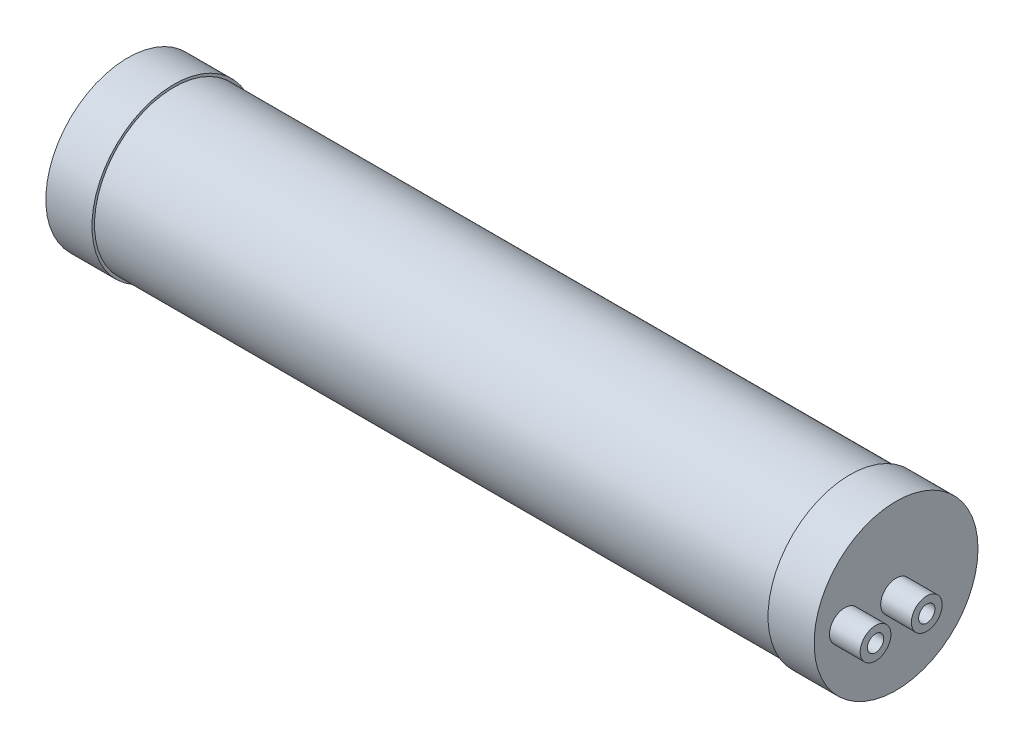
SolidWorks part; units mm, degrees
ref_plane "Front Plane" through (0, 0, 0) normal (0, 0, 1) x (1, 0, 0)
ref_plane "Top Plane" through (0, 0, 0) normal (0, 1, 0) x (1, 0, 0)
ref_plane "Right Plane" through (0, 0, 0) normal (1, 0, 0) x (0, 0, -1)
other "Configuration Table"
sketch "Sketch1" plane through (0, 0, 0) normal (1, 0, 0) x (0, 0, -1)
  circle A0 centre (0, 0) radius 31
  dimension "D1" = 62
extrude "Body" add sketch "Sketch1" along normal blind 300 from offset 150
sketch "Sketch2" plane through (0, 0, 0) normal (1, 0, 0) x (0, 0, -1)
  circle A0 centre (0, 0) radius 32
  dimension "D1" = 64
extrude "End_Cap_In" add sketch "Sketch2" along normal blind 18 from offset 150
sketch "Sketch3" plane through (0, 0, 0) normal (1, 0, 0) x (0, 0, -1)
  circle A0 centre (0, 0) radius 32
  dimension "D1" = 64
extrude "End_Cap_Out" add sketch "Sketch3" along normal blind 18 from offset 132
sketch "Sketch4" plane through (0, 0, 0) normal (1, 0, 0) x (0, 0, -1)
  circle A0 centre (0, 0) radius 6
  dimension "D1" = 12
extrude "Inlet_Port" add sketch "Sketch4" along normal blind 12 from offset 162
sketch "Sketch5" plane through (0, 0, 0) normal (1, 0, 0) x (0, 0, -1)
  circle A0 centre (0, 0) radius 3.2
  dimension "D1" = 6.4
extrude "Inlet_Socket" cut sketch "Sketch5" along normal blind 10 from offset 162
sketch "Sketch6" plane through (0, 0, 0) normal (1, 0, 0) x (0, 0, -1)
  circle A0 centre (0, 0) radius 6
  dimension "D1" = 12
extrude "Outlet_Port" add sketch "Sketch6" along normal blind 12 from offset 150
sketch "Sketch7" plane through (0, 0, 0) normal (1, 0, 0) x (0, 0, -1)
  circle A0 centre (0, 0) radius 3.2
  dimension "D1" = 6.4
extrude "Outlet_Socket" cut sketch "Sketch7" against normal blind 10 from offset 162
sketch "Sketch8" plane through (0, 0, 0) normal (1, 0, 0) x (0, 0, -1)
  circle A0 centre (-20, 0) radius 6
  dimension "D1" = 12
extrude "Reject_Port" add sketch "Sketch8" along normal blind 12 from offset 150
sketch "Sketch9" plane through (0, 0, 0) normal (1, 0, 0) x (0, 0, -1)
  circle A0 centre (-20, 0) radius 3.2
  dimension "D1" = 6.4
extrude "Reject_Socket" cut sketch "Sketch9" against normal blind 10 from offset 162
equation "\"Jar_OD\"= 90  'ASSUMED - Part G fallback - jar outer diameter"
equation "\"Jar_H\"= 120  'ASSUMED - Part G fallback - jar height"
equation "\"Pump_L\"= 45  'ASSUMED - Part G fallback"
equation "\"Pump_W\"= 24  'ASSUMED - Part G fallback"
equation "\"Pump_H\"= 33  'ASSUMED - Part G fallback"
equation "\"Pump_Outlet_OD\"= 7.5  'ASSUMED - Part G fallback"
equation "\"Tube_OD\"= 8  'ASSUMED - Part G fallback"
equation "\"Tube_ID\"= 6  'ASSUMED - Part G fallback"
equation "\"TDS_Body_Dia\"= 12  'ASSUMED - Part G fallback"
equation "\"TDS_Wet_Len\"= 45  'ASSUMED - Part G fallback - length in water"
equation "\"DS_Tube_Dia\"= 6  'ASSUMED - Part G fallback"
equation "\"DS_Tube_Len\"= 50  'ASSUMED - Part G fallback"
equation "\"ORP_Body_Dia\"= 12  'ASSUMED - Part G fallback"
equation "\"ORP_Body_Len\"= 150  'ASSUMED - Part G fallback"
equation "\"ORP_Cap_Dia\"= 16  'ASSUMED - Part G fallback"
equation "\"Turb_W\"= 33  'ASSUMED - Part G fallback - head width"
equation "\"Turb_D\"= 28  'ASSUMED - Part G fallback - head depth"
equation "\"Turb_H\"= 30  'ASSUMED - Part G fallback - head height"
equation "\"Turb_Slot_W\"= 10  'ASSUMED - Part G fallback - slot width"
equation "\"Flow_L\"= 62  'ASSUMED - Part G fallback YF-S201"
equation "\"Flow_W\"= 36  'ASSUMED - Part G fallback"
equation "\"Flow_H\"= 35  'ASSUMED - Part G fallback"
equation "\"Thread_G12_OD\"= 20.955  'ASSUMED - Part G fallback thread G1/2 (major diameter)"
equation "\"Valve_L\"= 75  'ASSUMED - Part G fallback"
equation "\"Valve_W\"= 45  'ASSUMED - Part G fallback"
equation "\"Valve_H\"= 60  'ASSUMED - Part G fallback"
equation "\"Tee_L\"= 40  'ASSUMED - Part G fallback - overall length"
equation "\"Tee_Branch_L\"= 25  'ASSUMED - Part G fallback"
equation "\"Tee_OD\"= 12  'ASSUMED - Part G fallback"
equation "\"LED_Board_L\"= 20  'ASSUMED - Part G fallback"
equation "\"LED_Board_W\"= 20  'ASSUMED - Part G fallback - LED at centre"
equation "\"GUVA_L\"= 20  'ASSUMED - Part G fallback"
equation "\"GUVA_W\"= 12  'ASSUMED - Part G fallback - sensor at centre"
equation "\"Reed_L\"= 27  'ASSUMED - Part G fallback MC-38 half"
equation "\"Reed_W\"= 14  'ASSUMED - Part G fallback"
equation "\"Reed_H\"= 8  'ASSUMED - Part G fallback"
equation "\"ESP_L\"= 51  'ASSUMED - Part G fallback"
equation "\"ESP_W\"= 28  'ASSUMED - Part G fallback"
equation "\"TFT_L\"= 58  'ASSUMED - Part G fallback - board"
equation "\"TFT_W\"= 35  'ASSUMED - Part G fallback - board"
equation "\"TFT_Win_L\"= 35  'ASSUMED - Part G fallback - visible window"
equation "\"TFT_Win_W\"= 28  'ASSUMED - Part G fallback - visible window"
equation "\"Relay_L\"= 50  'ASSUMED - Part G fallback"
equation "\"Relay_W\"= 26  'ASSUMED - Part G fallback"
equation "\"Relay_H\"= 19  'ASSUMED - Part G fallback"
equation "\"Mosfet_L\"= 34  'ASSUMED - Part G fallback"
equation "\"Mosfet_W\"= 17  'ASSUMED - Part G fallback"
equation "\"Mosfet_H\"= 12  'ASSUMED - Part G fallback"
equation "\"TDS_Board_L\"= 42  'ASSUMED - Part G fallback"
equation "\"TDS_Board_W\"= 32  'ASSUMED - Part G fallback"
equation "\"Turb_Board_L\"= 38  'ASSUMED - Part G fallback"
equation "\"Turb_Board_W\"= 28  'ASSUMED - Part G fallback"
equation "\"BNC_Thread_Dia\"= 9.5  'ASSUMED - Part G fallback"
equation "\"Plate_L\"= 420  'ASSUMED - Part G fallback"
equation "\"Plate_W\"= 297  'ASSUMED - Part G fallback"
equation "\"Plate_T\"= 6  'ASSUMED - Part G fallback"
equation "\"Booster_L\"= 150  'ASSUMED - Part G fallback - booster pump"
equation "\"Booster_W\"= 95  'ASSUMED - Part G fallback"
equation "\"Booster_H\"= 100  'ASSUMED - Part G fallback"
equation "\"PTube_OD\"= 6.35  'ASSUMED - Part G fallback - product tube 1/4 inch"
equation "\"Qz_Out\"= 12  'ASSUMED - Part G fallback - quartz channel outside square"
equation "\"Qz_Path\"= 10  'ASSUMED - Part G fallback - quartz channel inside light path"
equation "\"Qz_L\"= 40  'ASSUMED - Part G fallback - quartz channel length"
equation "\"LED860_Dia\"= 5  'ASSUMED - Part G fallback - 860 nm LED"
equation "\"BPW_L\"= 5.4  'ASSUMED - Part G fallback - BPW34"
equation "\"BPW_W\"= 4.3  'ASSUMED - Part G fallback - BPW34"
equation "\"Cart_Dia\"= 50  'ASSUMED - Part G fallback - sediment and pre-carbon cartridges"
equation "\"Cart_L\"= 255  'ASSUMED - Part G fallback"
equation "\"UF_Dia\"= 50  'ASSUMED - Part G fallback - UF cartridge"
equation "\"UF_L\"= 260  'ASSUMED - Part G fallback"
equation "\"RO_Dia\"= 62  'ASSUMED - Part G fallback - RO membrane housing"
equation "\"RO_L\"= 300  'ASSUMED - Part G fallback"
equation "\"UVC_Dia\"= 40  'ASSUMED - Part G fallback - UV-C chamber"
equation "\"UVC_L\"= 300  'ASSUMED - Part G fallback"
equation "\"Tank_W\"= 260  'ASSUMED - Part G fallback - storage tank"
equation "\"Tank_D\"= 160  'ASSUMED - Part G fallback"
equation "\"Tank_H\"= 300  'ASSUMED - Part G fallback"
equation "\"Cab_W\"= 400  'ASSUMED - Part G fallback - purifier cabinet"
equation "\"Cab_D\"= 270  'ASSUMED - Part G fallback"
equation "\"Cab_H\"= 560  'ASSUMED - Part G fallback"
equation "\"ORP_Board_L\"= 40  'ASSUMED - Part G fallback - ORP buffer board"
equation "\"ORP_Board_W\"= 30  'ASSUMED - Part G fallback"
equation "\"Opt_Board_L\"= 50  'ASSUMED - Part G fallback - optical front-end board"
equation "\"Opt_Board_W\"= 40  'ASSUMED - Part G fallback"
equation "\"Buck_L\"= 43  'ASSUMED - Part G fallback - 12 V to 5 V buck module"
equation "\"Buck_W\"= 21  'ASSUMED - Part G fallback"
equation "\"Buck_H\"= 14  'ASSUMED - Part G fallback"
equation "\"BB_L\"= 165  'ASSUMED - Part G fallback - breadboard (As_Built_R3 only)"
equation "\"BB_W\"= 55  'ASSUMED - Part G fallback"
equation "\"BB_H\"= 10  'ASSUMED - Part G fallback"
equation "\"Cuv_W\"= 12.5  'ASSUMED - old R3 cuvette (station suppressed in SS4)"
equation "\"Cuv_D\"= 12.5  'ASSUMED - old R3 cuvette (station suppressed in SS4)"
equation "\"Cuv_H\"= 45  'ASSUMED - old R3 cuvette (station suppressed in SS4)"
equation "\"Probe_Clr\"= 0.3  'DESIGN VALUE - Part C rule 3 - printed probe hole = diameter + 0.3"
equation "\"Label_H\"= 0.6  'DESIGN VALUE - Part D - raised label height"
